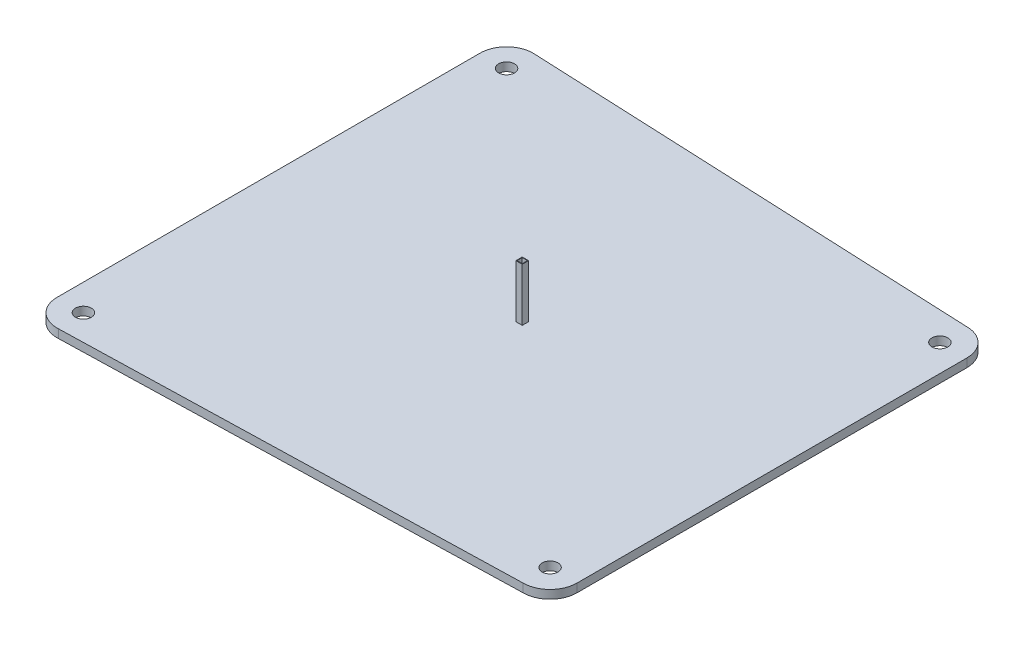
SolidWorks part; units mm, degrees
material "A-Glass Fiber"
ref_plane "Front Plane" through (0, 0, 0) normal (0, 0, 1) x (1, 0, 0)
ref_plane "Top Plane" through (0, 0, 0) normal (0, 1, 0) x (1, 0, 0)
ref_plane "Right Plane" through (0, 0, 0) normal (1, 0, 0) x (0, 0, -1)
sketch "Sketch1" plane through (0, 0, 0) normal (0, 1, 0) x (1, 0, 0)
  line L1 (-47.945, -45.085) -> (47.945, -45.085)
  line L2 (-47.945, -45.085) -> (-47.945, 45.085)
  line L3 (-47.945, 45.085) -> (47.945, 45.085)
  line L4 (47.945, -45.085) -> (47.945, 45.085)
  line L5 (-47.945, -45.085) -> (47.945, 45.085) construction
  line L6 (-47.945, 45.085) -> (47.945, -45.085) construction
  point P0 (0, 0)
  dimension "D1" = 95.89
  dimension "D2" = 90.17
extrude "Substrate" add sketch "Sketch1" along normal blind 1.6
sketch "Sketch2" plane through (0, 1.6, 0) normal (0, 1, 0) x (1, 0, 0)
  line L0 (-42.945, 39.9274) -> (-42.945, 50039.9274) construction
  line L2 (-47.945, -45.085) -> (47.945, -45.085) construction
  line L3 (-47.945, 45.085) -> (47.945, -45.085) construction
  line L4 (-47.945, 45.085) -> (-47.945, -45.085) construction
  line L5 (47.945, 45.085) -> (-47.945, 45.085) construction
  line L6 (47.945, -45.085) -> (47.945, 45.085) construction
  line L9 (47.945, -45.085) -> (-47.945, -45.085) construction
  circle A0 centre (42.845, 36.085) radius 1.5
  circle A1 centre (42.845, -37.585) radius 1.5
  circle A2 centre (-42.945, -39.985) radius 1.5
  circle A3 centre (-42.945, 39.985) radius 1.5
  dimension "D5" = 5.1
  dimension "D6" = 5
  dimension "D1" = 3
  dimension "D2" = 3
  dimension "D7" = 5.1
  dimension "D10" = 7.5
extrude "Cut-Extrude2" cut sketch "Sketch2" against normal blind 10
sketch "Sketch3" plane through (0, 1.6, 0) normal (0, 1, 0) x (1, 0, 0)
  line L0 (-47.945, 45.085) -> (47.945, -45.085) construction
  line L1 (-0.5, -0.5) -> (0.5, -0.5)
  line L2 (-0.5, -0.5) -> (-0.5, 0.5)
  line L3 (-0.5, 0.5) -> (0.5, 0.5)
  line L4 (0.5, -0.5) -> (0.5, 0.5)
  line L5 (-0.5, -0.5) -> (0.5, 0.5) construction
  line L6 (-0.5, 0.5) -> (0.5, -0.5) construction
  line L7 (-0.6, -0.6) -> (0.6, -0.6)
  line L8 (-0.6, -0.6) -> (-0.6, 0.6)
  line L9 (-0.6, 0.6) -> (0.6, 0.6)
  line L10 (0.6, -0.6) -> (0.6, 0.6)
  line L11 (-0.6, -0.6) -> (0.6, 0.6) construction
  line L12 (-0.6, 0.6) -> (0.6, -0.6) construction
  line L13 (47.945, -45.085) -> (47.945, 45.085) construction
  line L14 (47.945, 45.085) -> (-47.945, -45.085) construction
  point P0 (0, 0)
  point P6 (0, 0)
  dimension "D1" = 1
  dimension "D2" = 1
  dimension "D3" = 0.1
  dimension "D4" = 0.1
extrude "Centre Alignment" add sketch "Sketch3" along normal blind 10
sketch "Sketch4" plane through (0, 1.6, 0) normal (0, 1, 0) x (1, 0, 0)
  line L0 (-42.6771, -44.9778) -> (42.845, -42.685)
  line L1 (-47.945, -39.985) -> (-47.945, 39.985)
  line L2 (-42.5029, 44.9654) -> (42.845, 41.185)
  line L3 (47.945, 36.085) -> (47.945, -37.585)
  arc A0 (-47.945, -39.985) -> (-42.6771, -44.9778) centre (-42.945, -39.985) ccw
  arc A1 (-42.5029, 44.9654) -> (-47.945, 39.985) centre (-42.945, 39.985) ccw
  arc A2 (47.945, 36.085) -> (42.845, 41.185) centre (42.845, 36.085) ccw
  arc A3 (42.845, -42.685) -> (47.945, -37.585) centre (42.845, -37.585) ccw
extrude "Cut-Extrude3" cut sketch "Sketch4" against normal blind 10 flip side to cut
